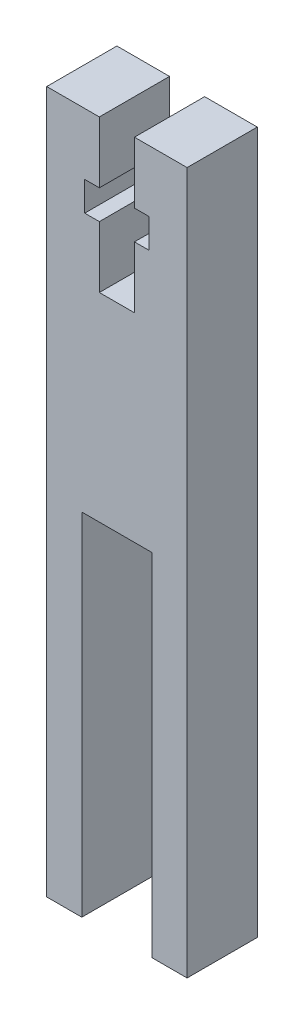
SolidWorks part; units mm, degrees
ref_plane "Спереди" through (0, 0, 0) normal (0, 0, 1) x (1, 0, 0)
ref_plane "Сверху" through (0, 0, 0) normal (0, 1, 0) x (1, 0, 0)
ref_plane "Справа" through (0, 0, 0) normal (1, 0, 0) x (0, 0, -1)
other "Configuration Table"
sketch "Эскиз1" plane through (0, 0, 0) normal (0, 0, 1) x (1, 0, 0)
  line L0 (0, 0) -> (0, 60) construction
  line L1 (0, 30) -> (-21.3565, 30) construction
  line L2 (-1.5, 60) -> (-1.5, 54.75)
  line L3 (-1.5, 54.75) -> (-2.75, 54.75)
  line L4 (-2.75, 54.75) -> (-2.75, 52.25)
  line L5 (-2.75, 52.25) -> (-1.5, 52.25)
  line L6 (-1.5, 52.25) -> (-1.5, 47)
  line L7 (-1.5, 47) -> (1.5, 47)
  line L8 (1.5, 52.25) -> (1.5, 47)
  line L9 (2.75, 52.25) -> (1.5, 52.25)
  line L10 (2.75, 54.75) -> (2.75, 52.25)
  line L11 (1.5, 54.75) -> (2.75, 54.75)
  line L12 (1.5, 60) -> (1.5, 54.75)
  line L25 (-1.5, 60) -> (-6, 60)
  line L26 (-6, 60) -> (-6, 0)
  line L28 (6, 60) -> (6, 0)
  line L29 (1.5, 60) -> (6, 60)
  line L30 (-6, 0) -> (-3, 0)
  line L31 (-3, 0) -> (-3, 30)
  line L32 (-3, 30) -> (3, 30)
  line L33 (3, 0) -> (3, 30)
  line L34 (6, 0) -> (3, 0)
  point P13 (0, 47)
  point P18 (2.75, 53.5)
  point P23 (0, 30)
  dimension "D1" = 2.5
  dimension "D2" = 3
  dimension "D3" = 5.5
  dimension "D4" = 13
  dimension "D5" = 6
  dimension "D6" = 12
  dimension "D7" = 60
extrude "Бобышка-Вытянуть1" add sketch "Эскиз1" along normal blind 6
